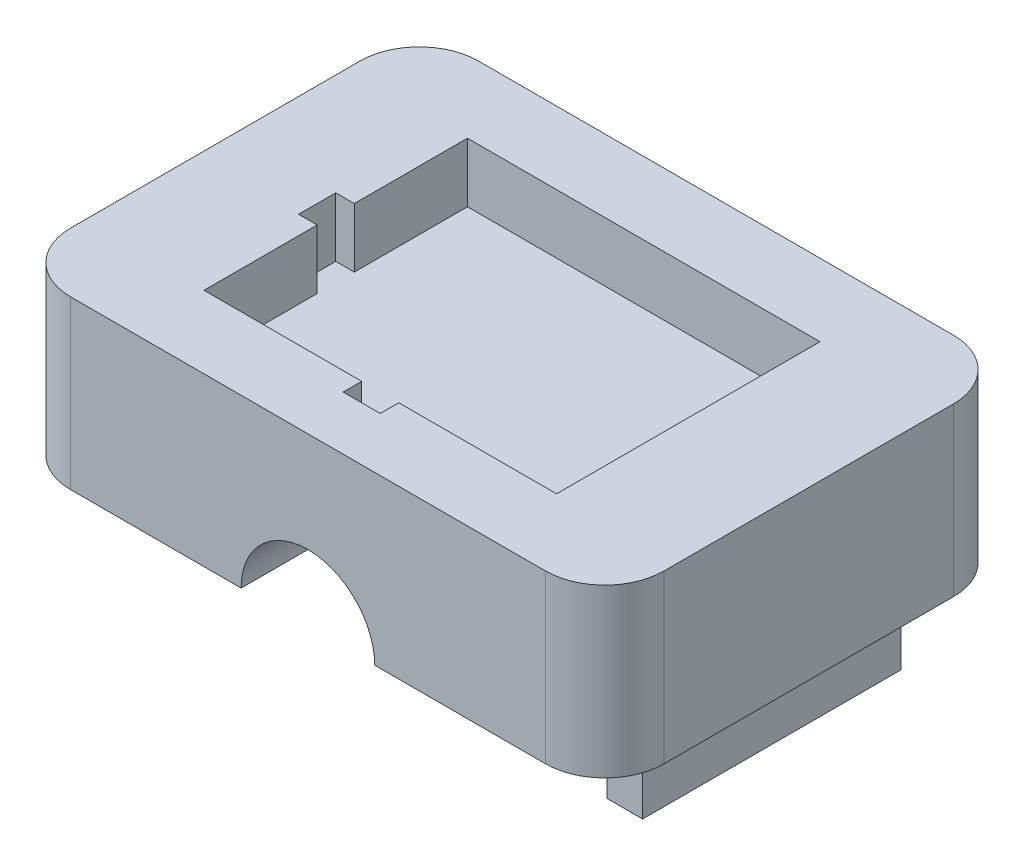
SolidWorks part; units mm, degrees
ref_plane "Alzado" through (0, 0, 0) normal (0, 0, 1) x (1, 0, 0)
ref_plane "Planta" through (0, 0, 0) normal (0, 1, 0) x (1, 0, 0)
ref_plane "Vista lateral" through (0, 0, 0) normal (1, 0, 0) x (0, 0, -1)
sketch "Croquis1" plane through (0, 0, 0) normal (0, 0, 1) x (1, 0, 0)
  line L0 (-9, 0) -> (-40, 0)
  line L1 (40, 0) -> (9, 0)
  line L2 (40, 0) -> (40, 22.5)
  line L3 (40, 22.5) -> (-40, 22.5)
  line L4 (-40, 0) -> (-40, 22.5)
  circle A0 centre (0, 0) radius 9
  dimension "D5" = 18
  dimension "D1" = 40
  dimension "D2" = 80
  dimension "D3" = 22.5
  dimension "D4" = 0
  dimension "D6" = 0
extrude "Saliente-Extruir1" add sketch "Croquis1" along normal blind 55 contours A0 L1 L2 L3 L4 L0
ref_plane "Plano1" through (0, 0, 27.5) normal (0, 0, 1) x (1, 0, 0)
sketch "Croquis2" plane through (0, 0, 27.5) normal (0, 0, 1) x (1, 0, 0)
  circle A0 centre (0, 0) radius 13.5
  dimension "D1" = 27
extrude "Cortar-Extruir1" cut sketch "Croquis2" against normal mid plane 8.1
sketch "Croquis3" plane through (0, 0, 0) normal (0, -1, 0) x (1, 0, 0)
  line L0 (0, 58.6648) -> (0, -5.1304) construction
  line L1 (-35, 44.9) -> (-30.2, 44.9)
  line L2 (-35, 44.9) -> (-35, 10.1)
  line L3 (-35, 10.1) -> (-30.2, 10.1)
  line L4 (-30.2, 44.9) -> (-30.2, 10.1)
  line L5 (-40, 55) -> (-40, 0) construction
  line L6 (-9, 55) -> (-40, 55) construction
  line L11 (40, 55) -> (9, 55) construction
  line L12 (30.2, 10.1) -> (35, 10.1)
  line L13 (30.2, 10.1) -> (30.2, 44.9)
  line L14 (30.2, 44.9) -> (35, 44.9)
  line L15 (35, 10.1) -> (35, 44.9)
  line L16 (30.2, 10.1) -> (35, 44.9) construction
  line L17 (30.2, 44.9) -> (35, 10.1) construction
  line L18 (40, 55) -> (40, 0) construction
  point P9 (-30.2, 27.5)
  point P12 (32.6, 27.5)
  dimension "D1" = 4.8
  dimension "D2" = 5
  dimension "D3" = 34.8
  dimension "D4" = 27.5
  dimension "D5" = 34.8
  dimension "D6" = 27.5
  dimension "D7" = 4.8
  dimension "D8" = 5
extrude "Saliente-Extruir2" add sketch "Croquis3" along normal blind 10
sketch "Croquis6" plane through (0, 22.5, 0) normal (0, 1, 0) x (1, 0, 0)
  line L18 (-40, -27.5) -> (-26.25, -27.5) construction
  line L19 (-40, -55) -> (-40, 0) construction
  line L21 (-23.75, -45.25) -> (-2.5, -45.25)
  line L22 (-23.75, -45.25) -> (-23.75, -30)
  line L23 (-23.75, -9.75) -> (23.75, -9.75)
  line L24 (23.75, -45.25) -> (23.75, -9.75)
  line L25 (-23.75, -25) -> (-23.75, -9.75)
  line L26 (2.5, -45.25) -> (23.75, -45.25)
  line L27 (-23.75, -25) -> (-26.25, -25)
  line L28 (-26.25, -25) -> (-26.25, -30)
  line L29 (-26.25, -30) -> (-23.75, -30)
  line L32 (-2.5, -45.25) -> (-2.5, -47.75)
  line L33 (-2.5, -47.75) -> (2.5, -47.75)
  line L34 (2.5, -47.75) -> (2.5, -45.25)
  line L36 (0, -27.5) -> (53.1647, -27.5) construction
  point P4 (0, -27.5)
  dimension "D1" = 47.5
  dimension "D2" = 35.5
  dimension "D3" = 15.25
  dimension "D4" = 21.25
  dimension "D5" = 2.5
  dimension "D8" = 2.5
fillet "Redondeo1" radius 8 4 edges at (40, 11.25, 0) (40, 11.25, 55) (-40, 11.25, 55) (-40, 11.25, 0)
extrude "Cortar-Extruir2" cut sketch "Croquis6" against normal blind 8
